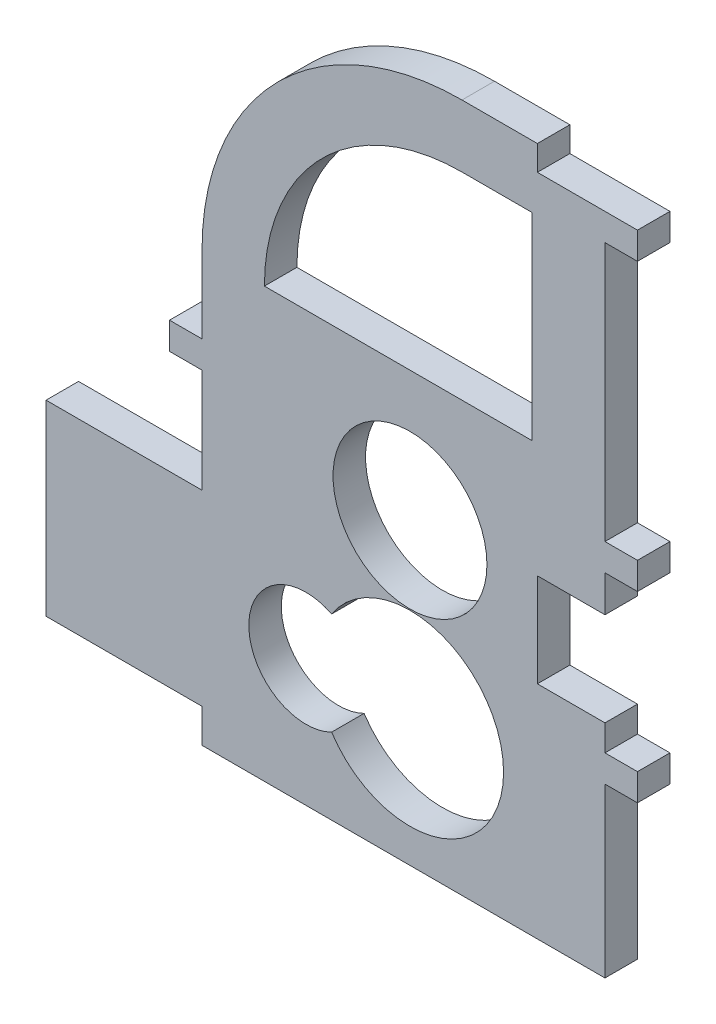
SolidWorks part; units mm, degrees
material "Balsa"
ref_plane "Front Plane" through (0, 0, 0) normal (0, 0, 1) x (1, 0, 0)
ref_plane "Top Plane" through (0, 0, 0) normal (0, 1, 0) x (1, 0, 0)
ref_plane "Right Plane" through (0, 0, 0) normal (1, 0, 0) x (0, 0, -1)
sketch "Sketch1" plane through (0, 0, 0) normal (0, 0, 1) x (1, 0, 0)
  line L0 (0, -1000) -> (0, 49000) construction
  line L1 (-1000, 0) -> (49000, 0) construction
  line L2 (0, -8.382) -> (-5.08, -8.382)
  line L3 (9.525, 16.51) -> (11.1125, 16.51)
  line L4 (2.54, 19.05) -> (9.525, 19.05)
  line L5 (9.525, -14.605) -> (-10.16, -14.605)
  line L6 (-10.16, -14.605) -> (-10.16, 6.35)
  line L7 (9.525, 19.05) -> (9.525, -14.605)
  line L8 (-11.7475, 1.27) -> (-10.16, 1.27)
  line L9 (-11.7475, 1.27) -> (-11.7475, 2.5908)
  line L10 (-11.7475, 2.5908) -> (-10.16, 2.5908)
  line L11 (-10.16, 1.27) -> (-10.16, 2.5908)
  line L12 (9.525, 2.54) -> (11.1125, 2.54)
  line L13 (9.525, 2.54) -> (9.525, 3.8608)
  line L14 (9.525, 3.8608) -> (11.1125, 3.8608)
  line L15 (11.1125, 2.54) -> (11.1125, 3.8608)
  line L16 (9.525, 16.51) -> (9.525, 17.8308)
  line L17 (9.525, 17.8308) -> (11.1125, 17.8308)
  line L18 (11.1125, 16.51) -> (11.1125, 17.8308)
  line L19 (-7.112, 6.35) -> (5.969, 6.35)
  line L20 (-10.16, -12.954) -> (-17.78, -12.954)
  line L21 (5.969, 6.35) -> (5.969, 16.002)
  line L22 (-10.16, -3.81) -> (-17.78, -3.81)
  line L23 (-17.78, -12.954) -> (-17.78, -3.81)
  line L24 (5.969, 16.002) -> (2.54, 16.002)
  line L27 (9.525, -6.4008) -> (11.1125, -6.4008)
  line L28 (9.525, -6.4008) -> (9.525, -5.08)
  line L29 (9.525, -5.08) -> (11.1125, -5.08)
  line L30 (11.1125, -6.4008) -> (11.1125, -5.08)
  circle A0 centre (0, 0) radius 3.7592
  arc A1 (-3.829, -10.8803) -> (-3.829, -5.8837) centre (0, -8.382) ccw
  arc A2 (-3.829, -5.8837) -> (-3.829, -10.8803) centre (-5.08, -8.382) ccw
  arc A3 (2.54, 19.05) -> (-10.16, 6.35) centre (2.54, 6.35) ccw
  arc A4 (2.54, 16.002) -> (-7.112, 6.35) centre (2.54, 6.35) ccw
  arc A5 (2.54, 19.05) -> (-10.16, 6.35) centre (2.54, 6.35) ccw construction
  dimension "D1" = 7.5184
  dimension "D4" = 9.144
  dimension "D3" = 19.685
  dimension "D5" = 8.382
  dimension "D9" = 12.7
  dimension "D10" = 1.5875
  dimension "D16" = 3.81
  dimension "D7" = 5.588
  dimension "D6" = 5.08
  dimension "D8" = 9.525
  dimension "D11" = 9.144
  dimension "D12" = 1.3208
  dimension "D13" = 1.3208
  dimension "D14" = 1.5875
  dimension "D15" = 2
  dimension "D17" = 14.605
  dimension "D18" = 19.05
  dimension "D19" = 16.51
  dimension "D20" = 3.048
  dimension "D21" = 3.556
  dimension "D22" = 1.3208
  dimension "D23" = 1.5875
  dimension "D24" = 5.08
  dimension "D25" = 1.27
  dimension "D26" = 7.62
  dimension "D27" = 2.54
extrude "Boss-Extrude1" add sketch "Sketch1" along normal blind 1.5875
sketch "Sketch2" plane through (0, 0, 1.5875) normal (0, 0, 1) x (1, 0, 0)
  line L1 (6.223, -3.81) -> (9.525, -3.81)
  line L2 (6.223, -3.81) -> (6.223, 0.762)
  line L3 (6.223, 0.762) -> (9.525, 0.762)
  line L4 (9.525, -3.81) -> (9.525, 0.762)
  line L5 (9.525, 2.54) -> (9.525, -5.08) construction
  line L7 (9.525, 19.05) -> (9.525, 17.8308) construction
  line L9 (6.223, 17.8308) -> (9.525, 17.8308)
  line L10 (6.223, 17.8308) -> (6.223, 21.59)
  line L11 (6.223, 21.59) -> (9.525, 21.59)
  line L12 (9.525, 17.8308) -> (9.525, 21.59)
  line L13 (9.525, 17.8308) -> (11.1125, 17.8308) construction
  point P9 (9.525, -1.524)
  point P10 (9.525, 19.7104)
  point P15 (9.525, 19.7104)
  dimension "D1" = 4.572
  dimension "D2" = 3.302
  dimension "D3" = 3.7592
  dimension "D4" = 3.302
  dimension "D5" = 0.762
extrude "Cut-Extrude1" cut sketch "Sketch2" against normal up to next
